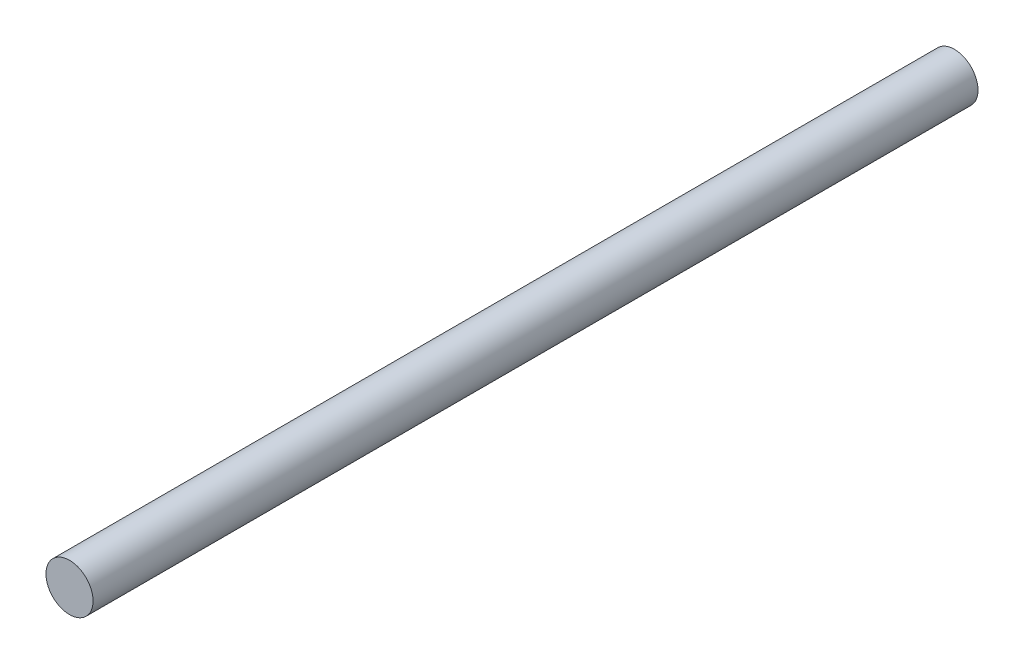
SolidWorks part; units mm, degrees
ref_plane "Front Plane" through (0, 0, 0) normal (0, 0, 1) x (1, 0, 0)
ref_plane "Top Plane" through (0, 0, 0) normal (0, 1, 0) x (1, 0, 0)
ref_plane "Right Plane" through (0, 0, 0) normal (1, 0, 0) x (0, 0, -1)
sketch "Sketch1" plane through (0, 0, 0) normal (0, 0, 1) x (1, 0, 0)
  circle A0 centre (0, 0) radius 3.9
extrude "Boss-Extrude1" add sketch "Sketch1" along normal blind 146.5
